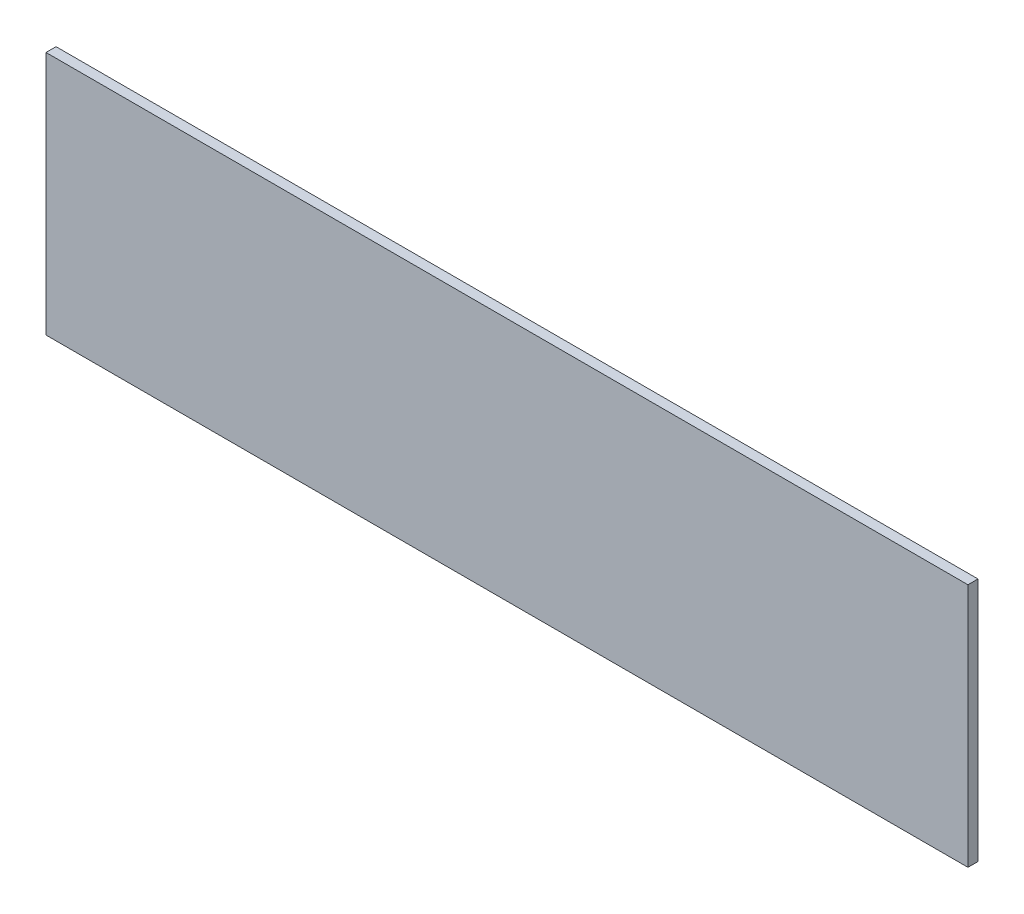
SolidWorks part; units mm, degrees
material "MDF"
ref_plane "Alzado" through (0, 0, 0) normal (0, 0, 1) x (1, 0, 0)
ref_plane "Planta" through (0, 0, 0) normal (0, 1, 0) x (1, 0, 0)
ref_plane "Vista lateral" through (0, 0, 0) normal (1, 0, 0) x (0, 0, -1)
sketch "Croquis1" plane through (0, 0, 0) normal (0, 0, 1) x (1, 0, 0)
  line L1 (-137.5, 36.5) -> (137.5, 36.5)
  line L2 (-137.5, 36.5) -> (-137.5, -36.5)
  line L3 (-137.5, -36.5) -> (137.5, -36.5)
  line L4 (137.5, 36.5) -> (137.5, -36.5)
  line L5 (-137.5, 36.5) -> (137.5, -36.5) construction
  line L6 (-137.5, -36.5) -> (137.5, 36.5) construction
  point P0 (0, 0)
  dimension "D1" = 73
  dimension "D2" = 275
extrude "Saliente-Extruir1" add sketch "Croquis1" along normal blind 3
